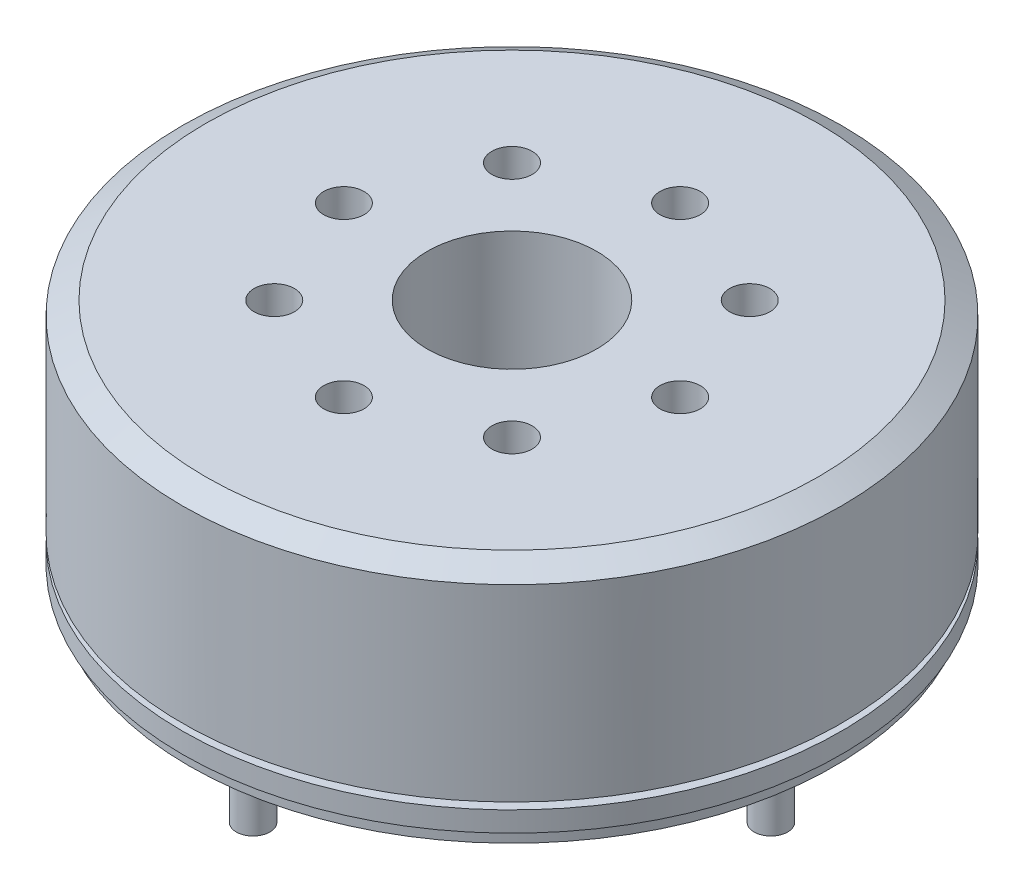
SolidWorks part; units mm, degrees
ref_plane "前视基准面" through (0, 0, 0) normal (0, 0, 1) x (1, 0, 0)
ref_plane "上视基准面" through (0, 0, 0) normal (0, 1, 0) x (1, 0, 0)
ref_plane "右视基准面" through (0, 0, 0) normal (1, 0, 0) x (0, 0, -1)
sketch "草图1" plane through (0, 0, 0) normal (0, 1, 0) x (1, 0, 0)
  circle A0 centre (0, 0) radius 24.5
extrude "凸台-拉伸1" add sketch "草图1" along normal blind 17
sketch "草图3" plane through (0, 0, 0) normal (1, 0, 0) x (0, 0, -1)
  line L2 (-23.5, 2.004) -> (-23.5, 1.5)
  line L6 (-23.5, 2.004) -> (-25.8375, 2.004)
  line L7 (-25.8375, 2.004) -> (-25.8375, 1.5)
  line L8 (-25.8375, 1.5) -> (-23.5, 1.5)
  line L9 (-24.5, 0) -> (24.5, 0) construction
  line L10 (-24.5, 17) -> (-24.5, 0) construction
  line L11 (0, 0) -> (0, 26.1688) construction
  dimension "D1" = 1.5
  dimension "D2" = 0.504
  dimension "D3" = 1
revolve "切除-旋转1" cut sketch "草图3" angle 360 about L11
chamfer "倒角1" distance 1 angle 60 1 edges at (0, 17, 24.5)
sketch "草图4" plane through (0, 0, 0) normal (0, -1, 0) x (1, 0, 0)
  circle A0 centre (0, 0) radius 24
extrude "凸台-拉伸2" add sketch "草图4" along normal blind 1
sketch "草图5" plane through (0, -1, 0) normal (0, -1, 0) x (1, 0, 0)
  circle A0 centre (0, 0) radius 8.3
extrude "凸台-拉伸3" add sketch "草图5" along normal blind 1
sketch "草图6" plane through (0, 17, 0) normal (0, 1, 0) x (1, 0, 0)
  circle A0 centre (0, 0) radius 6.3
extrude "切除-拉伸1" cut sketch "草图6" against normal blind 14
sketch "草图7" plane through (0, 3, 0) normal (0, 1, 0) x (1, 0, 0)
  circle A0 centre (0, 0) radius 4
extrude "切除-拉伸2" cut sketch "草图7" against normal blind 3
sketch "草图8" plane through (0, 0, 0) normal (0, 1, 0) x (1, 0, 0)
  circle A0 centre (0, 0) radius 2.5
extrude "切除-拉伸3" cut sketch "草图8" against normal up to surface (2 mm away) up to face at (0, -2, -8.3)
sketch "草图9" plane through (0, 17, 0) normal (0, 1, 0) x (1, 0, 0)
  circle A0 centre (0, 12.5) radius 1.5
  dimension "D1" = 12.5
extrude "切除-拉伸4" cut sketch "草图9" against normal blind 3
pattern_circular "阵列(圆周)1" count 8 over 360 about axis through (0, 0, 0) along (0, 1, 0) of "切除-拉伸4"
sketch "草图12" plane through (0, -1, 0) normal (0, -1, 0) x (1, 0, 0)
  circle A0 centre (0, 15) radius 1.5
  dimension "D1" = 15
extrude "切除-拉伸5" cut sketch "草图12" against normal blind 3
pattern_circular "阵列(圆周)2" count 4 over 360 about axis through (0, 0, 0) along (0, 1, 0) of "切除-拉伸5"
sketch "草图15" plane through (0, -2, 0) normal (0, -1, 0) x (1, 0, 0)
  circle A0 centre (0, 5.1725) radius 1.25
extrude "切除-拉伸8" cut sketch "草图15" against normal blind 1
pattern_circular "阵列(圆周)4" count 4 over 360 about axis through (0, 0, 0) along (0, 1, 0) of "切除-拉伸8"
sketch "草图16" plane through (0, -1, 0) normal (0, -1, 0) x (1, 0, 0)
  circle A0 centre (0, 19.25) radius 1.25
  dimension "D1" = 2.5
  dimension "D2" = 19.25
extrude "凸台-拉伸4" add sketch "草图16" along normal blind 6
pattern_circular "阵列(圆周)5" count 4 over 360 about axis through (0, 0, 0) along (0, 1, 0) of "凸台-拉伸4"
